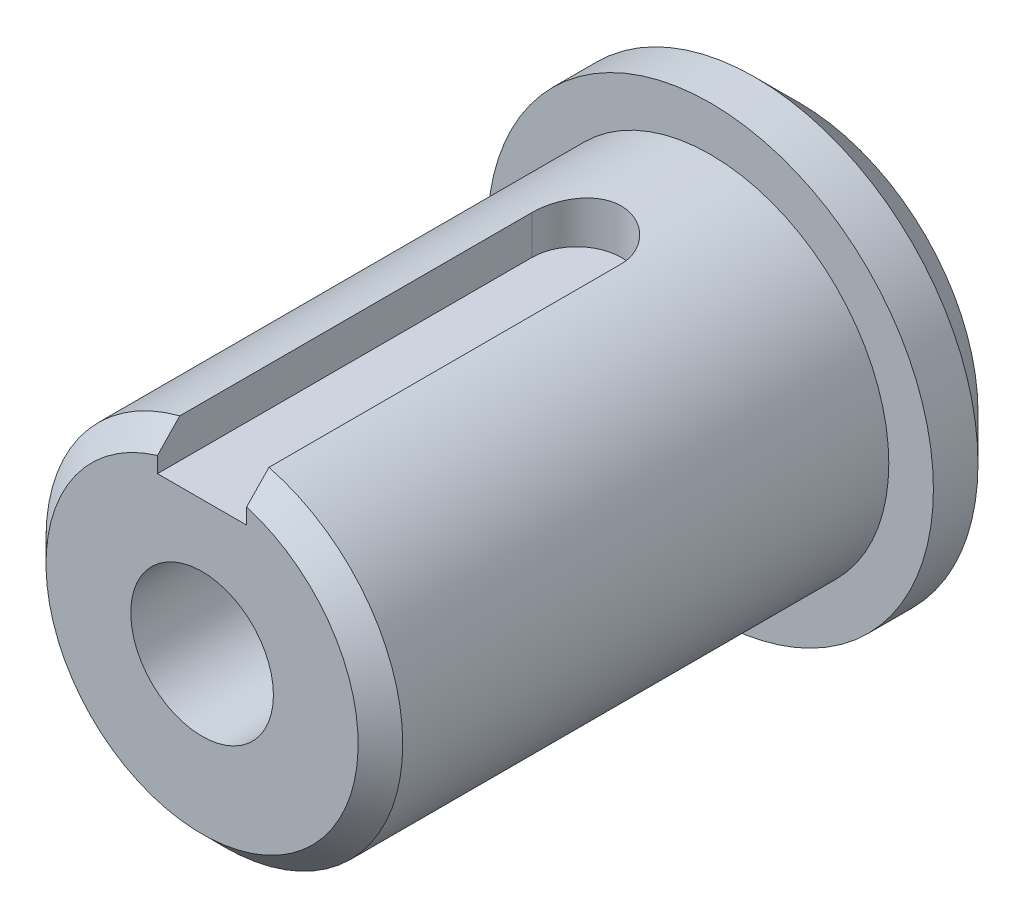
SolidWorks part; units mm, degrees
material "Plain Carbon Steel"
ref_plane "Front" through (0, 0, 0) normal (0, 0, 1) x (1, 0, 0)
ref_plane "Top" through (0, 0, 0) normal (0, 1, 0) x (1, 0, 0)
ref_plane "Right" through (0, 0, 0) normal (1, 0, 0) x (0, 0, -1)
sketch "Sketch1" plane through (0, 0, 0) normal (1, 0, 0) x (0, 0, -1)
  line L0 (0, 1.6) -> (0, 4)
  line L1 (0, 4) -> (-1, 5)
  line L2 (-1, 5) -> (-2, 5)
  line L3 (-2, 5) -> (-2, 4)
  line L4 (-2, 4) -> (-12.9, 4)
  line L5 (-12.9, 4) -> (-13.4, 3.5)
  line L6 (-13.4, 3.5) -> (-13.4, 1.6)
  line L7 (-13.4, 1.6) -> (0, 1.6)
  line L10 (0, 0) -> (3.2083, 0) construction
  dimension "D1" = 3.2
  dimension "D3" = 8
  dimension "D4" = 10
  dimension "D5" = 8
  dimension "D6" = 0.5
  dimension "D7" = 45
  dimension "D8" = 2
  dimension "D9" = 45
  dimension "D10" = 11.4
revolve "Revolve1" add sketch "Sketch1" angle 360 about L10
ref_plane "Plane1" through (0, 4, 0) normal (0, 1, 0) x (1, 0, 0)
sketch "Sketch2" plane through (0, 4, 0) normal (0, 1, 0) x (1, 0, 0)
  line L0 (0, -13.4) -> (0, -5) construction
  line L1 (-1, -13.4) -> (-1, -5)
  line L2 (1, -13.4) -> (1, -5)
  line L3 (-3.5, -13.4) -> (3.5, -13.4) construction
  arc A0 (-1, -13.4) -> (1, -13.4) centre (0, -13.4) ccw
  arc A1 (1, -5) -> (-1, -5) centre (0, -5) ccw
  point P3 (0, -9.2)
  dimension "D2" = 9.4
  dimension "D1" = 2
extrude "Cut-Extrude1" cut sketch "Sketch2" against normal blind 1
